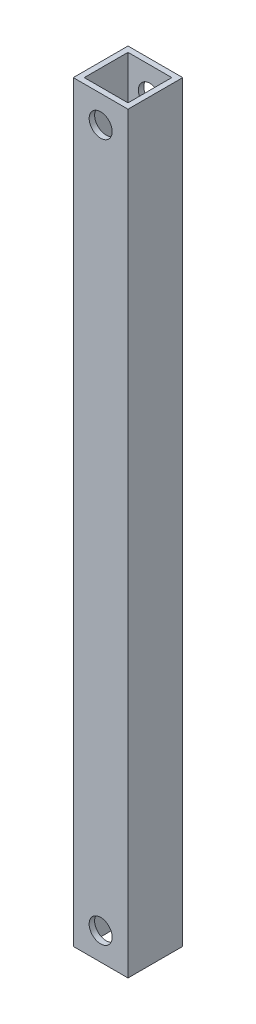
SolidWorks part; units mm, degrees
material "5052-H34"
ref_plane "正面" through (0, 0, 0) normal (0, 0, 1) x (1, 0, 0)
ref_plane "平面" through (0, 0, 0) normal (0, 1, 0) x (1, 0, 0)
ref_plane "右側面" through (0, 0, 0) normal (1, 0, 0) x (0, 0, -1)
sketch "ｽｹｯﾁ1" plane through (0, 0, 0) normal (0, 1, 0) x (1, 0, 0)
  line L1 (-5, -5) -> (5, -5)
  line L2 (-5, -5) -> (-5, 5)
  line L3 (-5, 5) -> (5, 5)
  line L4 (5, -5) -> (5, 5)
  line L5 (-5, -5) -> (5, 5) construction
  line L6 (-5, 5) -> (5, -5) construction
  point P0 (0, 0)
  dimension "D1" = 10
  dimension "D2" = 10
extrude "押し出し-薄板1" add sketch "ｽｹｯﾁ1" along normal blind 137.5 thin thin type one direction reverse wall 1
sketch "ｽｹｯﾁ2" plane through (0, 0, 5) normal (0, 0, 1) x (1, 0, 0)
  line L0 (0, 137.5) -> (0, 0) construction
  line L1 (-5, 137.5) -> (5, 137.5) construction
  line L2 (-5, 0) -> (5, 0) construction
  line L3 (5, 68.75) -> (-5, 68.75) construction
  line L4 (5, 137.5) -> (5, 0) construction
  line L5 (-5, 137.5) -> (-5, 0) construction
  circle A0 centre (0, 132.5) radius 2.1
  circle A1 centre (0, 5) radius 2.1
  dimension "D1" = 5
  dimension "D2" = 4.2
extrude "ｶｯﾄ - 押し出し1" cut sketch "ｽｹｯﾁ2" against normal up to surface (10 mm away) up to face at (0, 68.75, -5)
